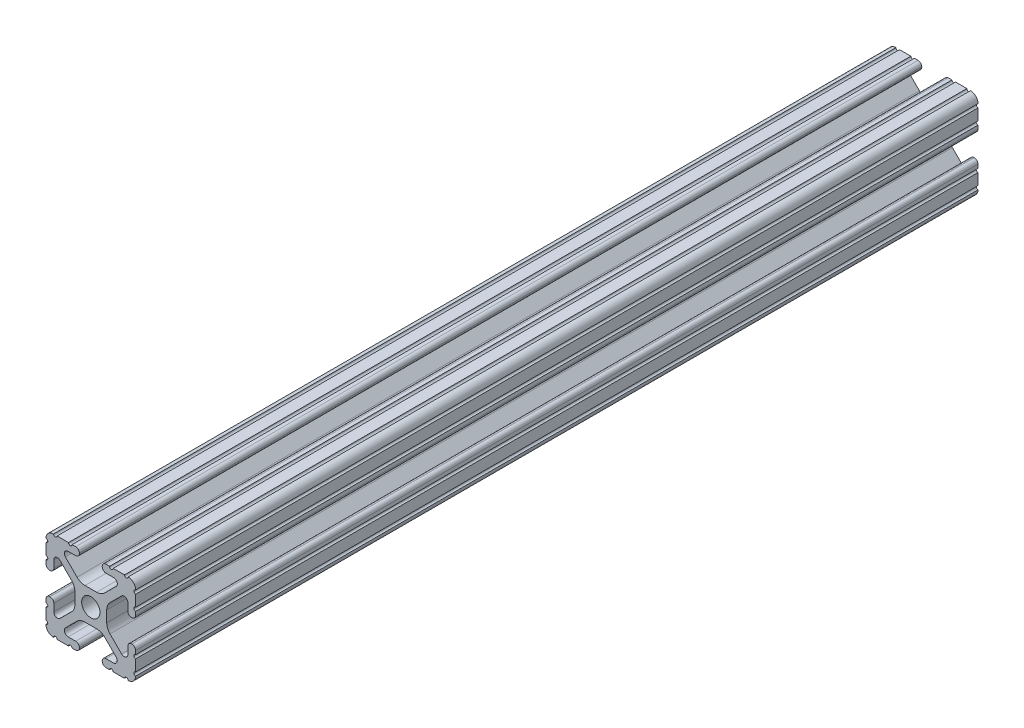
SolidWorks part; units mm, degrees
ref_plane "Front Plane" through (0, 0, 0) normal (0, 0, 1) x (1, 0, 0)
ref_plane "Top Plane" through (0, 0, 0) normal (0, 1, 0) x (1, 0, 0)
ref_plane "Right Plane" through (0, 0, 0) normal (1, 0, 0) x (0, 0, -1)
sketch "Sketch1" plane through (0, 0, 0) normal (0, 0, 1) x (1, 0, 0)
  line L88 (-7.1797, -8.6452) -> (-3.9523, -5.4237)
  line L89 (-1.7093, -4.4958) -> (1.7093, -4.4958)
  line L90 (3.9523, -5.4237) -> (7.1797, -8.6452)
  line L91 (6.4164, -10.4902) -> (4.2875, -10.4902)
  line L92 (3.2385, -11.5392) -> (3.2385, -11.651)
  line L93 (4.2875, -12.7) -> (5.3171, -12.7)
  line L94 (6.3331, -12.7) -> (9.5504, -12.7)
  line L95 (12.7, -9.5504) -> (12.7, -6.3331)
  line L96 (12.7, -5.3171) -> (12.7, -4.2875)
  line L97 (11.651, -3.2385) -> (11.5392, -3.2385)
  line L98 (10.4902, -4.2875) -> (10.4902, -6.4021)
  line L99 (8.7371, -7.1294) -> (5.441, -3.8408)
  line L100 (4.5085, -1.5932) -> (4.5085, 1.5932)
  line L101 (5.441, 3.8408) -> (8.7371, 7.1294)
  line L102 (10.4902, 6.4021) -> (10.4902, 4.2875)
  line L103 (11.5392, 3.2385) -> (11.651, 3.2385)
  line L104 (12.7, 4.2875) -> (12.7, 5.3171)
  line L105 (12.7, 6.3331) -> (12.7, 9.5504)
  line L106 (9.5504, 12.7) -> (6.3331, 12.7)
  line L107 (5.3171, 12.7) -> (4.2875, 12.7)
  line L108 (3.2385, 11.651) -> (3.2385, 11.5392)
  line L109 (4.2875, 10.4902) -> (6.4768, 10.4902)
  line L110 (7.207, 8.7244) -> (3.8983, 5.4232)
  line L111 (1.6558, 4.4958) -> (-1.6558, 4.4958)
  line L112 (-3.8983, 5.4232) -> (-7.207, 8.7244)
  line L113 (-6.4768, 10.4902) -> (-4.2875, 10.4902)
  line L114 (-3.2385, 11.5392) -> (-3.2385, 11.651)
  line L115 (-4.2875, 12.7) -> (-5.3171, 12.7)
  line L116 (-6.3331, 12.7) -> (-9.5504, 12.7)
  line L117 (-12.7, 9.5504) -> (-12.7, 6.3331)
  line L118 (-12.7, 5.3171) -> (-12.7, 4.2875)
  line L119 (-11.651, 3.2385) -> (-11.5392, 3.2385)
  line L120 (-10.4902, 4.2875) -> (-10.4902, 6.4021)
  line L121 (-8.7371, 7.1294) -> (-5.441, 3.8408)
  line L122 (-4.5085, 1.5932) -> (-4.5085, -1.5932)
  line L123 (-5.441, -3.8408) -> (-8.7371, -7.1294)
  line L124 (-10.4902, -6.4021) -> (-10.4902, -4.2875)
  line L125 (-11.5392, -3.2385) -> (-11.651, -3.2385)
  line L126 (-12.7, -4.2875) -> (-12.7, -5.3171)
  line L127 (-12.7, -6.3331) -> (-12.7, -9.5504)
  line L128 (-9.5504, -12.7) -> (-6.3331, -12.7)
  line L129 (-5.3171, -12.7) -> (-4.2875, -12.7)
  line L130 (-3.2385, -11.651) -> (-3.2385, -11.5392)
  line L131 (-4.2875, -10.4902) -> (-6.4164, -10.4902)
  circle A1 centre (0, 0) radius 2.6035
  arc A104 (-7.1797, -8.6452) -> (-6.4164, -10.4902) centre (-6.4164, -9.4098) ccw
  arc A105 (-1.7093, -4.4958) -> (-3.9523, -5.4237) centre (-1.7093, -7.6708) ccw
  arc A106 (3.9523, -5.4237) -> (1.7093, -4.4958) centre (1.7093, -7.6708) ccw
  arc A107 (6.4164, -10.4902) -> (7.1797, -8.6452) centre (6.4164, -9.4098) ccw
  arc A108 (4.2875, -10.4902) -> (3.2385, -11.5392) centre (4.2875, -11.5392) ccw
  arc A109 (3.2385, -11.651) -> (4.2875, -12.7) centre (4.2875, -11.651) ccw
  arc A110 (6.3331, -12.7) -> (5.3171, -12.7) centre (5.8251, -12.7) ccw
  arc A111 (10.5664, -12.6998) -> (9.5504, -12.7) centre (10.0584, -12.7) ccw
  arc A112 (10.5664, -12.6998) -> (12.6998, -10.5664) centre (10.5918, -10.5918) ccw
  arc A113 (12.7, -9.5504) -> (12.6998, -10.5664) centre (12.7, -10.0584) ccw
  arc A114 (12.7, -5.3171) -> (12.7, -6.3331) centre (12.7, -5.8251) ccw
  arc A115 (12.7, -4.2875) -> (11.651, -3.2385) centre (11.651, -4.2875) ccw
  arc A116 (11.5392, -3.2385) -> (10.4902, -4.2875) centre (11.5392, -4.2875) ccw
  arc A117 (8.7371, -7.1294) -> (10.4902, -6.4021) centre (9.4628, -6.4021) ccw
  arc A118 (4.5085, -1.5932) -> (5.441, -3.8408) centre (7.6835, -1.5932) ccw
  arc A119 (5.441, 3.8408) -> (4.5085, 1.5932) centre (7.6835, 1.5932) ccw
  arc A120 (10.4902, 6.4021) -> (8.7371, 7.1294) centre (9.4628, 6.4021) ccw
  arc A121 (10.4902, 4.2875) -> (11.5392, 3.2385) centre (11.5392, 4.2875) ccw
  arc A122 (11.651, 3.2385) -> (12.7, 4.2875) centre (11.651, 4.2875) ccw
  arc A123 (12.7, 6.3331) -> (12.7, 5.3171) centre (12.7, 5.8251) ccw
  arc A124 (12.6998, 10.5664) -> (12.7, 9.5504) centre (12.7, 10.0584) ccw
  arc A125 (12.6998, 10.5664) -> (10.5664, 12.6998) centre (10.5918, 10.5918) ccw
  arc A126 (9.5504, 12.7) -> (10.5664, 12.6998) centre (10.0584, 12.7) ccw
  arc A127 (5.3171, 12.7) -> (6.3331, 12.7) centre (5.8251, 12.7) ccw
  arc A128 (4.2875, 12.7) -> (3.2385, 11.651) centre (4.2875, 11.651) ccw
  arc A129 (3.2385, 11.5392) -> (4.2875, 10.4902) centre (4.2875, 11.5392) ccw
  arc A130 (7.207, 8.7244) -> (6.4768, 10.4902) centre (6.4768, 9.4563) ccw
  arc A131 (1.6558, 4.4958) -> (3.8983, 5.4232) centre (1.6558, 7.6708) ccw
  arc A132 (-3.8983, 5.4232) -> (-1.6558, 4.4958) centre (-1.6558, 7.6708) ccw
  arc A133 (-6.4768, 10.4902) -> (-7.207, 8.7244) centre (-6.4768, 9.4563) ccw
  arc A134 (-4.2875, 10.4902) -> (-3.2385, 11.5392) centre (-4.2875, 11.5392) ccw
  arc A135 (-3.2385, 11.651) -> (-4.2875, 12.7) centre (-4.2875, 11.651) ccw
  arc A136 (-6.3331, 12.7) -> (-5.3171, 12.7) centre (-5.8251, 12.7) ccw
  arc A137 (-10.5664, 12.6998) -> (-9.5504, 12.7) centre (-10.0584, 12.7) ccw
  arc A138 (-10.5664, 12.6998) -> (-12.6998, 10.5664) centre (-10.5918, 10.5918) ccw
  arc A139 (-12.7, 9.5504) -> (-12.6998, 10.5664) centre (-12.7, 10.0584) ccw
  arc A140 (-12.7, 5.3171) -> (-12.7, 6.3331) centre (-12.7, 5.8251) ccw
  arc A141 (-12.7, 4.2875) -> (-11.651, 3.2385) centre (-11.651, 4.2875) ccw
  arc A142 (-11.5392, 3.2385) -> (-10.4902, 4.2875) centre (-11.5392, 4.2875) ccw
  arc A143 (-8.7371, 7.1294) -> (-10.4902, 6.4021) centre (-9.4628, 6.4021) ccw
  arc A144 (-4.5085, 1.5932) -> (-5.441, 3.8408) centre (-7.6835, 1.5932) ccw
  arc A145 (-5.441, -3.8408) -> (-4.5085, -1.5932) centre (-7.6835, -1.5932) ccw
  arc A146 (-10.4902, -6.4021) -> (-8.7371, -7.1294) centre (-9.4628, -6.4021) ccw
  arc A147 (-10.4902, -4.2875) -> (-11.5392, -3.2385) centre (-11.5392, -4.2875) ccw
  arc A148 (-11.651, -3.2385) -> (-12.7, -4.2875) centre (-11.651, -4.2875) ccw
  arc A149 (-12.7, -6.3331) -> (-12.7, -5.3171) centre (-12.7, -5.8251) ccw
  arc A150 (-12.6998, -10.5664) -> (-12.7, -9.5504) centre (-12.7, -10.0584) ccw
  arc A151 (-12.6998, -10.5664) -> (-10.5664, -12.6998) centre (-10.5918, -10.5918) ccw
  arc A152 (-9.5504, -12.7) -> (-10.5664, -12.6998) centre (-10.0584, -12.7) ccw
  arc A153 (-5.3171, -12.7) -> (-6.3331, -12.7) centre (-5.8251, -12.7) ccw
  arc A154 (-4.2875, -12.7) -> (-3.2385, -11.651) centre (-4.2875, -11.651) ccw
  arc A155 (-3.2385, -11.5392) -> (-4.2875, -10.4902) centre (-4.2875, -11.5392) ccw
extrude "Boss-Extrude1" add sketch "Sketch1" along normal mid plane 238.76
